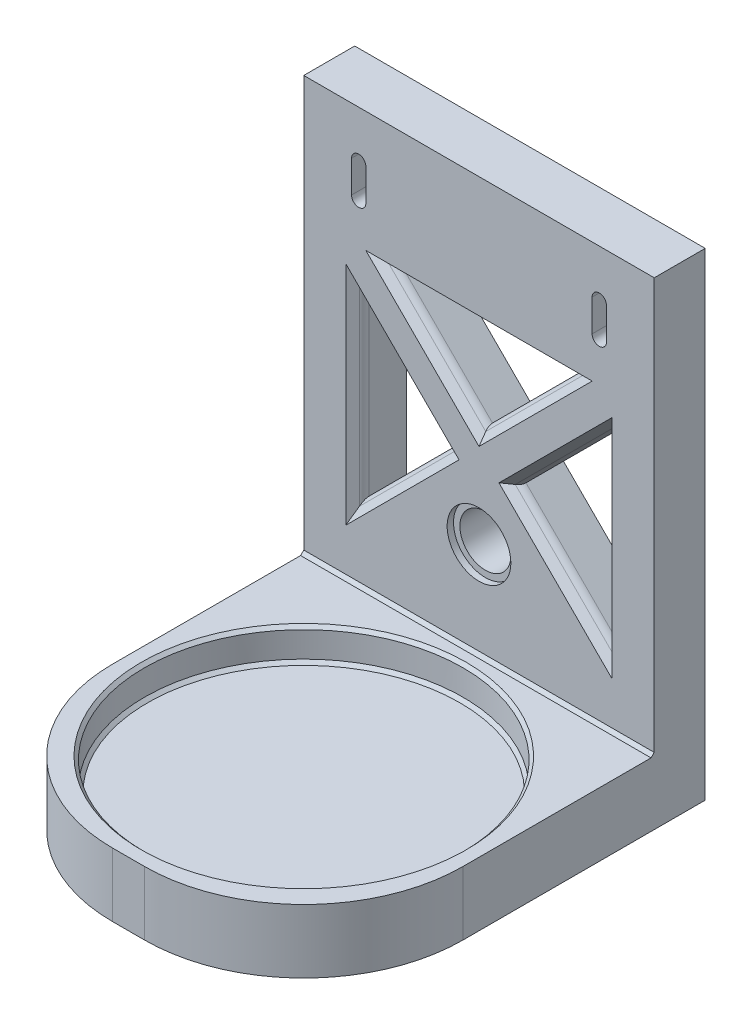
SolidWorks part; units mm, degrees
ref_plane "Front Plane" through (0, 0, 0) normal (0, 0, 1) x (1, 0, 0)
ref_plane "Top Plane" through (0, 0, 0) normal (0, 1, 0) x (1, 0, 0)
ref_plane "Right Plane" through (0, 0, 0) normal (1, 0, 0) x (0, 0, -1)
sketch "Sketch1" plane through (0, 0, 0) normal (0, 0, 1) x (1, 0, 0)
  line L0 (0, 150) -> (0, 0) construction
  line L1 (55, 0) -> (-55, 0)
  line L2 (55, 0) -> (55, 150)
  line L3 (55, 150) -> (-55, 150)
  line L4 (-55, 0) -> (-55, 150)
  line L5 (-37.75, 135) -> (-37.75, 125) construction
  line L6 (-35.5, 135) -> (-35.5, 125)
  line L7 (-40, 135) -> (-40, 125)
  line L8 (37.75, 135) -> (37.75, 125) construction
  line L9 (35.5, 135) -> (35.5, 125)
  line L10 (40, 135) -> (40, 125)
  arc A3 (-35.5, 135) -> (-40, 135) centre (-37.75, 135) ccw
  arc A4 (-40, 125) -> (-35.5, 125) centre (-37.75, 125) ccw
  arc A5 (35.5, 135) -> (40, 135) centre (37.75, 135) cw
  arc A6 (40, 125) -> (35.5, 125) centre (37.75, 125) cw
  point P11 (-37.75, 130)
  point P16 (37.75, 130)
  dimension "D3" = 4.5
  dimension "D4" = 10
  dimension "D6" = 15
  dimension "D1" = 150
  dimension "D2" = 110
  dimension "D7" = 15
extrude "Boss-Extrude1" add sketch "Sketch1" along normal blind 16
sketch "Sketch4" plane through (0, 0, 0) normal (0, 1, 0) x (1, 0, 0)
  line L0 (55, -16) -> (-55, -16) construction
  line L1 (-55, -16) -> (55, -16)
  line L2 (-55, -16) -> (-55, -126)
  line L3 (-55, -126) -> (55, -126)
  line L4 (55, -16) -> (55, -126)
  line L6 (0, -16) -> (0, -126) construction
  line L7 (-55, -71) -> (55, -71) construction
  dimension "D1" = 110
  dimension "D2" = 110
sketch "Sketch5" plane through (0, 0, 16) normal (0, 0, 1) x (1, 0, 0)
  line L0 (0, 0) -> (0, 150) construction
  line L1 (55, 150) -> (-55, 150) construction
  line L2 (-55, 75) -> (55, 75) construction
  line L3 (-55, 150) -> (-55, 0) construction
  line L4 (55, 0) -> (55, 150) construction
  circle A0 centre (0, 50) radius 10
  dimension "D1" = 20
  dimension "D2" = 50
extrude "Boss-Extrude2" add sketch "Sketch4" along normal blind 20 contours L2 L3 L4 L1
sketch "Sketch6" plane through (0, 20, 0) normal (0, 1, 0) x (1, 0, 0)
  line L0 (-10, -16) -> (10, -16) construction
  circle A0 centre (0, -71) radius 50
  point P0 (0, -21)
  point P1 (0, -16)
  dimension "D1" = 100
  dimension "D2" = 5
extrude "Cut-Extrude1" cut sketch "Sketch6" against normal blind 10 contours A0
fillet "Fillet1" radius 50 2 edges at (55, 10, 126) (-55, 10, 126)
sketch "Sketch7" plane through (0, 0, 16) normal (0, 0, 1) x (1, 0, 0)
  circle A0 centre (0, 50) radius 8
  dimension "D1" = 16
extrude "Cut-Extrude4" cut sketch "Sketch7" against normal through all
extrude "Cut-Extrude5" cut sketch "Sketch5" against normal blind 2
chamfer "Chamfer3" distance 1 angle 45 1 edges at (0, 20, 16)
chamfer "Chamfer4" distance 1 angle 45 2 edges at (0, 10, 121) (0, 20, 121)
sketch "Sketch8" plane through (0, 0, 16) normal (0, 0, 1) x (1, 0, 0)
  line L0 (-38.79, 98.1745) -> (-10.5057, 69.8902)
  line L1 (-10.5057, 69.8902) -> (-38.79, 41.6059)
  line L2 (-38.79, 41.6059) -> (-38.79, 98.1745)
  line L3 (0, 150) -> (0, 20) construction
  line L4 (55, 150) -> (-55, 150) construction
  line L5 (-5, 20) -> (5, 20) construction
  line L12 (10.5057, 69.8902) -> (38.79, 41.6059)
  line L13 (38.79, 98.1745) -> (10.5057, 69.8902)
  line L14 (38.79, 41.6059) -> (38.79, 98.1745)
  line L18 (28.2843, 109.1864) -> (0, 80.9021)
  line L19 (0, 80.9021) -> (-28.2843, 109.1864)
  line L20 (-28.2843, 109.1864) -> (28.2843, 109.1864)
  dimension "D1" = 40
  dimension "D2" = 40
  dimension "D3" = 40
  dimension "D4" = 40
extrude "Cut-Extrude7" cut sketch "Sketch8" against normal through all
chamfer "Chamfer6" distance 3 angle 45 9 edges at (24.6479, 55.7481, 16) (38.79, 69.8902, 16) (24.6479, 84.0323, 16) (-24.6479, 55.7481, 16) (-24.6479, 84.0323, 16) (-38.79, 69.8902, 16) (-14.1421, 95.0442, 16) (14.1421, 95.0442, 16) (0, 109.1864, 16)
fillet "Fillet3" radius 3 9 edges at (-24.6479, 55.7481, 13) (-24.6479, 84.0323, 13) (-38.79, 69.8902, 13) (-14.1421, 95.0442, 13) (0, 109.1864, 13) (14.1421, 95.0442, 13) (24.6479, 55.7481, 13) (24.6479, 84.0323, 13) (38.79, 69.8902, 13)
sketch "Sketch9" plane through (0, 10, 0) normal (0, 1, 0) x (1, 0, 0)
  line L0 (0, -22) -> (0, -120) construction
  line L1 (49, -71) -> (-49, -71) construction
  circle A0 centre (0, -71) radius 49 construction
  circle A1 centre (0, -37.2379) radius 3
  circle A3 centre (0, -71) radius 3
  point P9 (0, -37.2379)
  point P11 (-20.6485, -49.4957)
  point P12 (0, -71)
  point P14 (0, -71)
  dimension "D1" = 6
